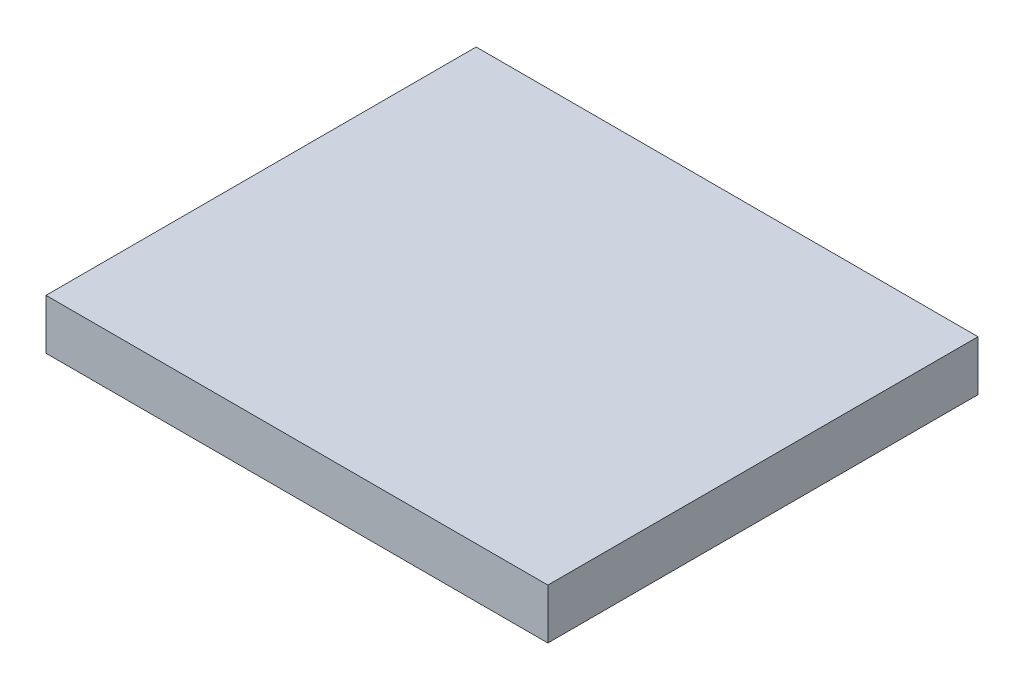
SolidWorks part; units mm, degrees
ref_plane "정면" through (0, 0, 0) normal (0, 0, 1) x (1, 0, 0)
ref_plane "윗면" through (0, 0, 0) normal (0, 1, 0) x (1, 0, 0)
ref_plane "우측면" through (0, 0, 0) normal (1, 0, 0) x (0, 0, -1)
sketch "스케치1" plane through (0, 0, 0) normal (0, 1, 0) x (1, 0, 0)
  line L1 (-17.5, -15) -> (17.5, -15)
  line L2 (-17.5, -15) -> (-17.5, 15)
  line L3 (-17.5, 15) -> (17.5, 15)
  line L4 (17.5, -15) -> (17.5, 15)
  line L5 (-17.5, -15) -> (17.5, 15) construction
  line L6 (-17.5, 15) -> (17.5, -15) construction
  point P0 (0, 0)
  dimension "D1" = 35
  dimension "D2" = 30
extrude "보스-돌출1" add sketch "스케치1" along normal blind 3.5
